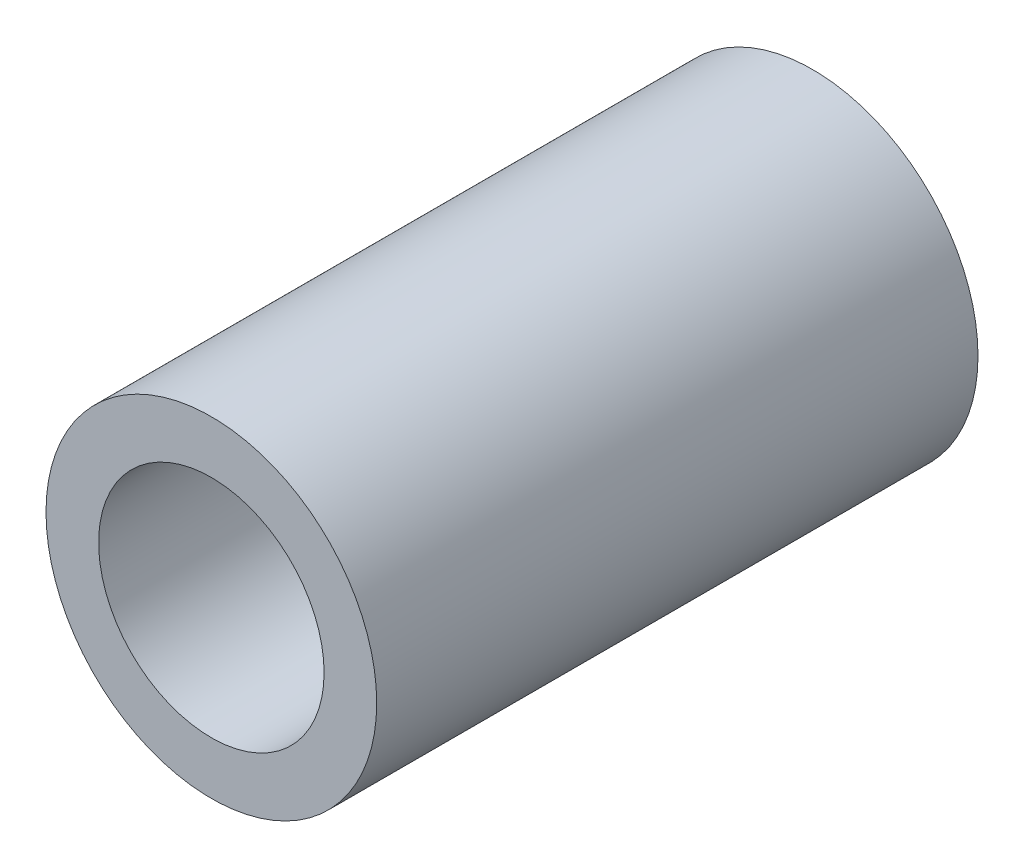
SolidWorks part; units mm, degrees
ref_plane "Front Plane" through (0, 0, 0) normal (0, 0, 1) x (1, 0, 0)
ref_plane "Top Plane" through (0, 0, 0) normal (0, 1, 0) x (1, 0, 0)
ref_plane "Right Plane" through (0, 0, 0) normal (1, 0, 0) x (0, 0, -1)
sketch "Sketch1" plane through (0, 0, 0) normal (0, 0, 1) x (1, 0, 0)
  circle A0 centre (-42.1496, 34.9398) radius 2.2
  circle A1 centre (-42.1496, 34.9398) radius 1.5
extrude "Boss-Extrude1" add sketch "Sketch1" along normal blind 8
